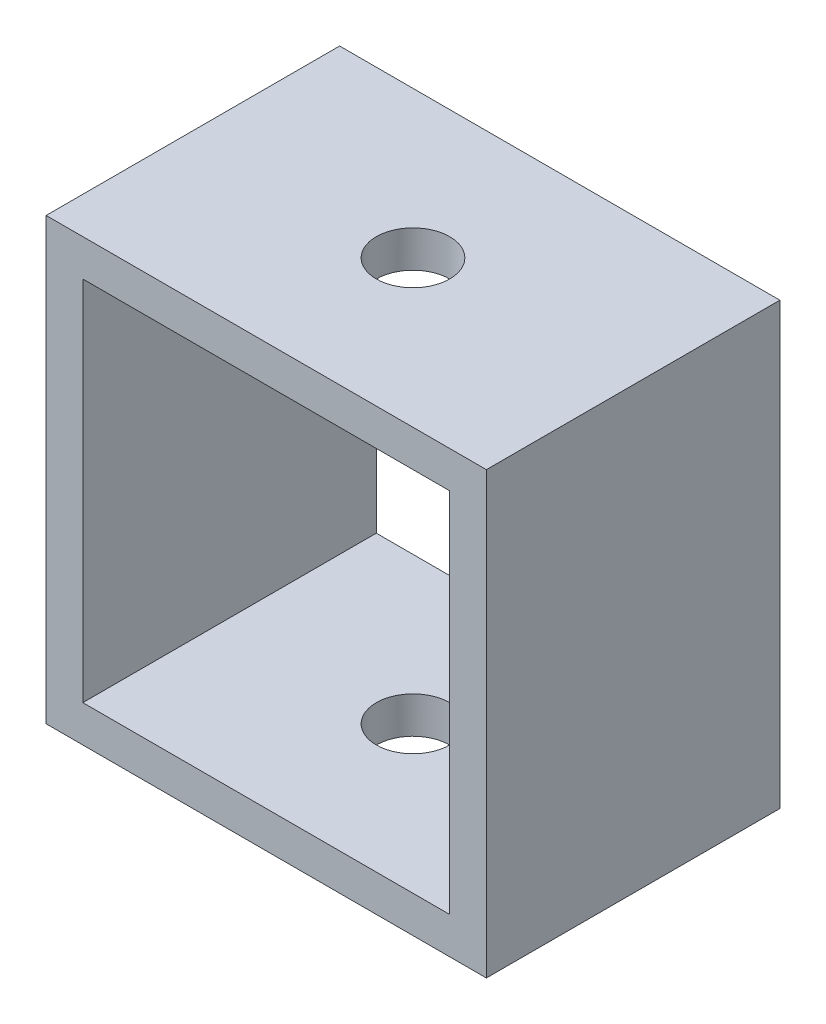
SolidWorks part; units mm, degrees
ref_plane "Front Plane" through (0, 0, 0) normal (0, 0, 1) x (1, 0, 0)
ref_plane "Top Plane" through (0, 0, 0) normal (0, 1, 0) x (1, 0, 0)
ref_plane "Right Plane" through (0, 0, 0) normal (1, 0, 0) x (0, 0, -1)
ref_plane "Plane1"
sketch "Sketch1" plane through (0, 0, 0) normal (0, 1, 0) x (-1, 0, 0)
  line L0 (-19.05, 12.7) -> (19.05, 12.7)
  line L1 (19.05, 12.7) -> (19.05, -12.7)
  line L2 (19.05, -12.7) -> (-19.05, -12.7)
  line L3 (-19.05, -12.7) -> (-19.05, 12.7)
  dimension "D1" = 38.1
  dimension "D2" = 25.4
extrude "Extrusion1" add sketch "Sketch1" along normal blind 38.1
shell "Shell1" thickness 3.175
hole_wizard "Hole1" positions "Sketch3" profile "Sketch2" legacy end condition through all
sketch "Sketch3" plane through (0, 38.1, 0) normal (0, 1, 0) x (1, 0, 0)
  point P1 (0, 0)
sketch "Sketch2" plane through (0, 38.1, 0) normal (1, 0, 0) x (0, 0, 1)
  line L0 (0, 0) -> (0, 38.1)
  line L1 (0, 38.1) -> (3.175, 38.1)
  line L2 (3.175, 38.1) -> (3.175, 0)
  line L3 (3.175, 0) -> (0, 0)
  line L4 (0, 110) -> (0, -10) construction
  dimension "Diameter" = 6.35
  dimension "Depth" = 38.1
sketch "Sketch4" plane through (0, 0, 12.7) normal (0, 0, 1) x (1, 0, 0)
  line L0 (-19.05, 0) -> (19.05, 0)
  line L1 (19.05, 0) -> (19.05, 38.1)
  line L2 (19.05, 38.1) -> (-19.05, 38.1)
  line L3 (-19.05, 38.1) -> (-19.05, 0)
  line L4 (15.875, 3.175) -> (-15.875, 3.175)
  line L5 (-15.875, 3.175) -> (-15.875, 34.925)
  line L6 (-15.875, 34.925) -> (15.875, 34.925)
  line L7 (15.875, 34.925) -> (15.875, 3.175)
extrude "Extrusion2" add sketch "Sketch4" along normal blind 5.3848
ref_plane "Plane2"
sketch "Sketch5" plane through (0, 38.1, 0) normal (0, 1, 0) x (1, 0, 0)
  line L0 (19.05, -18.0848) -> (19.05, -12.7)
  line L1 (19.05, -12.7) -> (-19.05, -12.7)
  line L2 (-19.05, -12.7) -> (-19.05, -18.0848)
  line L3 (-19.05, -18.0848) -> (19.05, -18.0848)
extrude "Extrusion3" cut sketch "Sketch5" against normal blind 38.1
